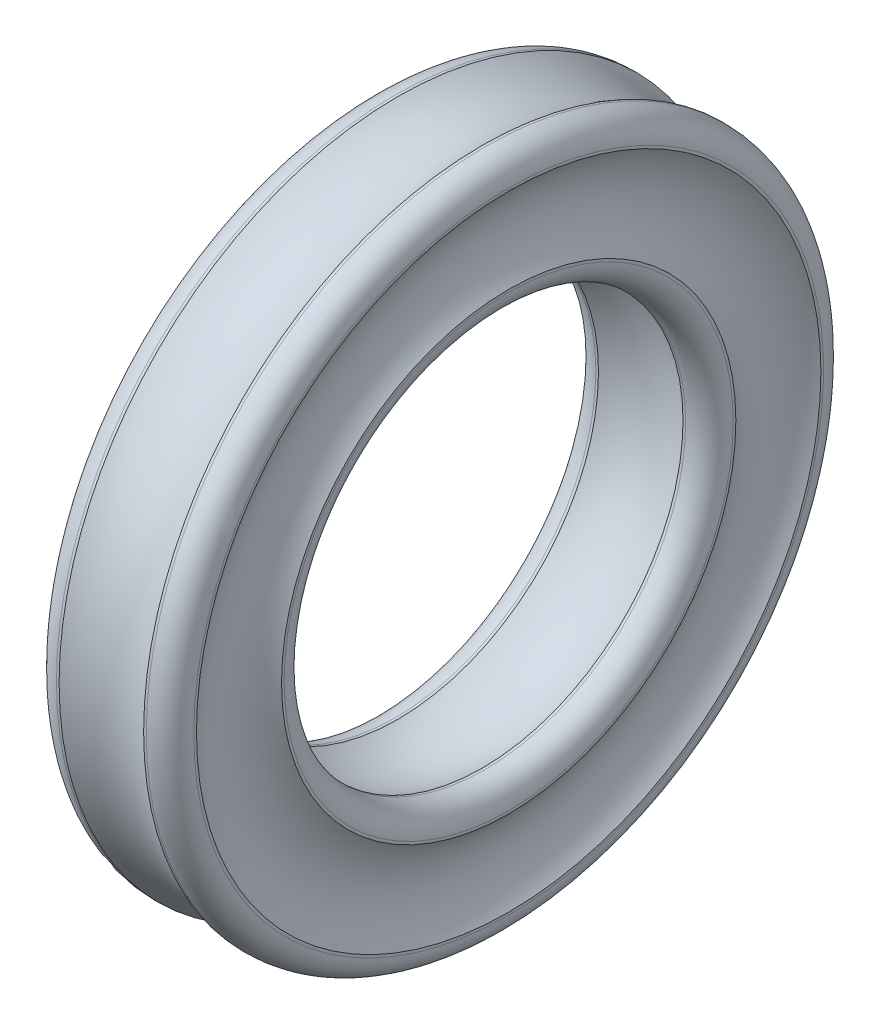
SolidWorks part; units mm, degrees
ref_plane "Front Plane" through (0, 0, 0) normal (0, 0, 1) x (1, 0, 0)
ref_plane "Top Plane" through (0, 0, 0) normal (0, 1, 0) x (1, 0, 0)
ref_plane "Right Plane" through (0, 0, 0) normal (1, 0, 0) x (0, 0, -1)
sketch "Sketch1" plane through (0, 0, 0) normal (0, 0, 1) x (1, 0, 0)
  line L0 (0, 0) -> (0.9665, 0) construction
  line L1 (-1.3, 3.8) -> (-0.8, 3.8)
  line L2 (-1.3, 3.8) -> (-1.3, 4.3)
  line L3 (-1.3, 6.41) -> (-0.8, 6.41)
  line L4 (1.3, 3.8) -> (1.3, 4.3)
  line L5 (-1.3, 3.8) -> (1.3, 6.41) construction
  line L6 (-1.3, 6.41) -> (1.3, 3.8) construction
  line L7 (-1.3, 5.91) -> (-1.3, 6.41)
  line L8 (0.8, 6.41) -> (1.3, 6.41)
  line L9 (1.3, 5.91) -> (1.3, 6.41)
  line L10 (0.8, 3.8) -> (1.3, 3.8)
  arc A0 (-1.3, 5.91) -> (-1.3, 4.3) centre (-2.3656, 5.105) cw
  arc A1 (1.3, 5.91) -> (1.3, 4.3) centre (2.3376, 5.105) ccw
  arc A2 (-0.8, 6.41) -> (0.8, 6.41) centre (0, 7.7925) ccw
  arc A3 (-0.8, 3.8) -> (0.8, 3.8) centre (0, 2.4175) cw
  point P0 (0, 5.105)
  dimension "D4" = 0.5
  dimension "D1" = 2.6
  dimension "D2" = 3.8
  dimension "D3" = 6.41
  dimension "D5" = 0.5
revolve "Revolve1" add sketch "Sketch1" angle 360 about L0
fillet "Fillet1" radius 0.45 4 edges at (-1.3, 0, 3.8) (-1.3, 0, 6.41) (1.3, 0, 3.8) (1.3, 0, 6.41)
